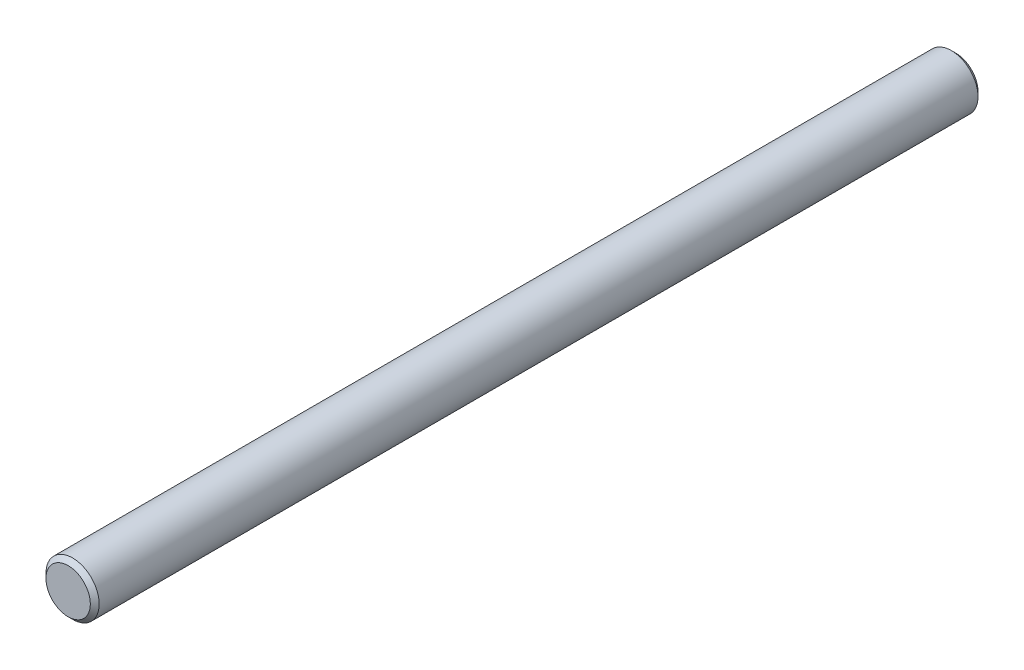
SolidWorks part; units mm, degrees
ref_plane "Front Plane" through (0, 0, 0) normal (0, 0, 1) x (1, 0, 0)
ref_plane "Top Plane" through (0, 0, 0) normal (0, 1, 0) x (1, 0, 0)
ref_plane "Right Plane" through (0, 0, 0) normal (1, 0, 0) x (0, 0, -1)
sketch "Sketch1" plane through (0, 0, 0) normal (0, 0, 1) x (1, 0, 0)
  circle A0 centre (0, 0) radius 3
  dimension "D1" = 6
extrude "Boss-Extrude1" add sketch "Sketch1" along normal blind 100
chamfer "Chamfer1" distance 0.5 angle 45 2 edges at (3, 0, 0) (3, 0, 100)
